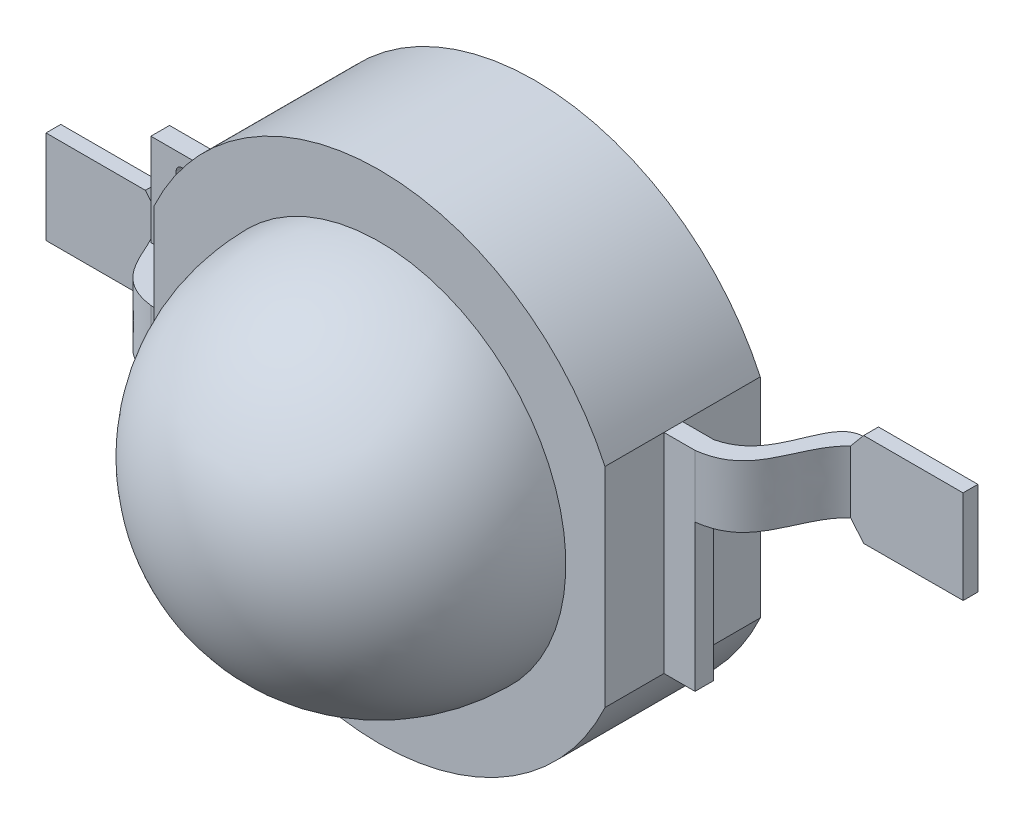
SolidWorks part; units mm, degrees
ref_plane "Front Plane" through (0, 0, 0) normal (0, 0, 1) x (1, 0, 0)
ref_plane "Top Plane" through (0, 0, 0) normal (0, 1, 0) x (1, 0, 0)
ref_plane "Right Plane" through (0, 0, 0) normal (1, 0, 0) x (0, 0, -1)
sketch "Sketch2" plane through (0, 0, 0) normal (0, 0, 1) x (1, 0, 0)
  line L0 (0, 3) -> (0, -3)
  arc A0 (0, 3) -> (0, -3) centre (0, 0) ccw
  dimension "D1" = 6
revolve "Revolve1" add sketch "Sketch2" angle 180 about L0
sketch "Sketch3" plane through (0, 0, 0) normal (0, 0, -1) x (-1, 0, 0)
  line L0 (-3.63, 0) -> (3.63, 0) construction
  line L1 (-3.63, 3.63) -> (3.63, 3.63)
  line L2 (-3.63, 3.63) -> (-3.63, -3.63)
  line L3 (-3.63, -3.63) -> (3.63, -3.63)
  line L4 (3.63, 3.63) -> (3.63, -3.63)
  line L5 (0, 3.63) -> (0, -3.63) construction
  arc A0 (-3.63, -1.6802) -> (3.63, -1.6802) centre (0, 0) ccw
  arc A1 (3.63, 1.6802) -> (-3.63, 1.6802) centre (0, 0) ccw
  point P11 (0, 0)
  circle M3 centre (0, 0) radius 3
  dimension "D1" = 8
  dimension "D2" = 7.26
  dimension "D3" = 7.26
extrude "Boss-Extrude1" add sketch "Sketch3" along normal blind 2.5 separate body contours L4 A1 L1 L2 A0 L3 M3 | L1 A1 | L3 A0
ref_plane "Plane1" through (0, 0, -1.25) normal (0, 0, 1) x (1, 0, 0)
sketch "Sketch4" plane through (0, 0, -1.25) normal (0, 0, 1) x (1, 0, 0)
  line L0 (-4.13, 1.3984) -> (-4.13, 0.3973) construction
  line L1 (-3.63, 1.6802) -> (-4.63, 1.6802)
  line L2 (-3.63, 1.6802) -> (-3.63, -1.6802)
  line L3 (-3.63, -1.6802) -> (-4.63, -1.6802)
  line L4 (-4.63, 1.6802) -> (-4.63, -1.6802)
  line L5 (-4.0371, 1.3984) -> (-4.0371, 0.3973)
  line L6 (-4.2229, 1.3984) -> (-4.2229, 0.3973)
  line L8 (-4.63, -0.6802) -> (-4.53, -0.6802)
  line L9 (-4.63, -0.6802) -> (-4.63, 0.197)
  line L10 (-4.63, 0.197) -> (-4.53, 0.197)
  line L11 (-4.53, -0.6802) -> (-4.53, 0.197)
  arc A0 (-4.0371, 1.3984) -> (-4.2229, 1.3984) centre (-4.13, 1.3984) ccw
  arc A1 (-4.2229, 0.3973) -> (-4.0371, 0.3973) centre (-4.13, 0.3973) ccw
  point P7 (-4.13, 0.8978)
  dimension "D1" = 1
  dimension "D2" = 1
  dimension "D3" = 0.1
extrude "Boss-Extrude2" add sketch "Sketch4" along normal blind 0.3 contours L11 L8 L4 L3 L2 L1 L10 A1 L6 A0 L5
sketch "Sketch5" plane through (0, -1.6802, 0) normal (0, -1, 0) x (1, 0, 0)
  line L0 (-5.8205, -2.2617) -> (-5.8205, -2.5)
  line L1 (-4.63, -0.95) -> (-4.63, -1.25)
  line L5 (-4.63, -1.25) -> (-3.63, -1.25)
  line L6 (-3.63, -1.25) -> (-3.63, -0.95)
  line L7 (-3.63, -0.95) -> (-4.63, -0.95)
  line L8 (-4.63, -0.95) -> (-4.63, -1.25)
  line L9 (-4.63, -1.25) -> (-3.63, -1.25)
  line L10 (-3.63, -1.25) -> (-3.63, -0.95)
  line L11 (-3.63, -0.95) -> (-4.63, -0.95)
  spline S0 degree 3 poles (-4.63, -1.25) (-5.4429, -1.435) (-5.2345, -2.5198) (-5.8205, -2.5) knots 0 0 0 0 0.623821 0.623821 0.623821 0.623821
  spline S1 degree 3 poles (-4.63, -0.95) (-5.4633, -1.0548) (-5.372, -1.8395) (-5.8205, -2.2617) knots 0 0 0 0 1 1 1 1
  line M8 (-4.63, -0.95) -> (-4.63, -1.25)
  dimension "D1" = 0
extrude "Boss-Extrude3" add sketch "Sketch5" against normal up to surface (1 mm away) contours S1 L0 S0 M8 up to face at (-4.58, -0.6802, -1.1)
ref_plane "Plane2" through (0, 0, -2.5) normal (0, 0, -1) x (-1, 0, 0)
sketch "Sketch6" plane through (0, 0, -2.5) normal (0, 0, -1) x (-1, 0, 0)
  line L0 (5.8205, -0.6802) -> (6.0303, -0.4302)
  line L1 (6.0303, -0.4302) -> (7.6303, -0.4302)
  line L2 (5.8205, -1.1802) -> (7.8769, -1.1802) construction
  line L3 (5.8205, -0.6802) -> (5.8205, -1.6802) construction
  line L4 (5.8205, -1.6802) -> (6.0303, -1.9302)
  line L5 (6.0303, -1.9302) -> (7.6303, -1.9302)
  line L6 (7.6303, -0.4302) -> (7.6303, -1.9302)
  line L7 (5.8205, -0.6802) -> (5.8205, -1.6802)
  dimension "D1" = 1.6
  dimension "D2" = 0.75
extrude "Boss-Extrude4" add sketch "Sketch6" against normal up to vertex (0.2383 mm away)
sketch "Sketch8" plane through (0, 0, -1.25) normal (0, 0, 1) x (1, 0, 0)
  line L1 (3.63, 1.6802) -> (4.13, 1.6802)
  line L2 (3.63, 1.6802) -> (3.63, -1.6802)
  line L3 (3.63, -1.6802) -> (4.13, -1.6802)
  line L4 (4.13, 1.6802) -> (4.13, -1.6802)
  dimension "D1" = 0.5
extrude "Boss-Extrude5" add sketch "Sketch8" along normal blind 0.3
sketch "Sketch9" plane through (0, 1.6802, 0) normal (0, 1, 0) x (1, 0, 0)
  line L0 (4.13, 1.25) -> (4.13, 0.95)
  line L1 (5.3205, 2.5) -> (5.3205, 2.2617)
  line L4 (-3.63, 1.25) -> (-4.63, 1.25)
  line L5 (-3.63, 0.95) -> (-3.63, 1.25)
  line L6 (-4.63, 0.95) -> (-3.63, 0.95)
  line L7 (-5.8205, 2.5) -> (-5.8205, 2.2617)
  line L8 (-3.63, 1.25) -> (-4.63, 1.25)
  line L9 (-3.63, 0.95) -> (-3.63, 1.25)
  line L10 (-4.63, 0.95) -> (-3.63, 0.95)
  spline S0 degree 3 poles (4.13, 1.25) (4.9429, 1.435) (4.7345, 2.5198) (5.3205, 2.5) knots 0 0 0 0 0.623821 0.623821 0.623821 0.623821
  spline S1 degree 3 poles (5.3205, 2.2617) (4.872, 1.8395) (4.9633, 1.0548) (4.13, 0.95) knots 0 0 0 0 1 1 1 1
  spline S2 degree 3 poles (-830.5968, -563.1937) (810.1378, 586.6877) (-819.8008, -585.296) (815.7772, 572.6982) knots -7.86991 -7.86991 -7.86991 -7.86991 8.594164 8.594164 8.594164 8.594164 only from (-5.8205, 2.2617) to (-4.63, 0.95)
  spline S3 degree 3 poles (692.3316, 718.3575) (-684.3019, -741.9738) (662.0858, 756.6188) (-668.1699, -746.668) knots -4.173095 -4.173095 -4.173095 -4.173095 4.7978 4.7978 4.7978 4.7978 only from (-4.63, 1.25) to (-5.8205, 2.5)
  line M11 (4.13, 0.95) -> (4.13, 1.25)
  dimension "D1" = 0
extrude "Boss-Extrude6" add sketch "Sketch9" against normal blind 1 contours S1 L1 S0 M11
sketch "Sketch10" plane through (0, 0, -2.5) normal (0, 0, -1) x (-1, 0, 0)
  line L0 (-5.3205, 1.6802) -> (-5.5326, 1.933)
  line L1 (-5.5326, 1.933) -> (-7.1326, 1.933)
  line L2 (-7.1326, 1.933) -> (-7.1349, 0.433)
  line L3 (-5.3205, 1.1802) -> (-7.1326, 1.183) construction
  line L4 (-5.3205, 0.6802) -> (-5.3205, 1.6802) construction
  line L6 (-5.5349, 0.4281) -> (-7.1349, 0.433)
  line L7 (-5.322, 0.6802) -> (-5.5349, 0.4281)
  line L8 (-5.3205, 1.6802) -> (-5.322, 0.6802)
  dimension "D1" = 0.33
  dimension "D2" = 1.6
  dimension "D3" = 0.75
extrude "Boss-Extrude7" add sketch "Sketch10" against normal up to vertex (0.2383 mm away) separate body
